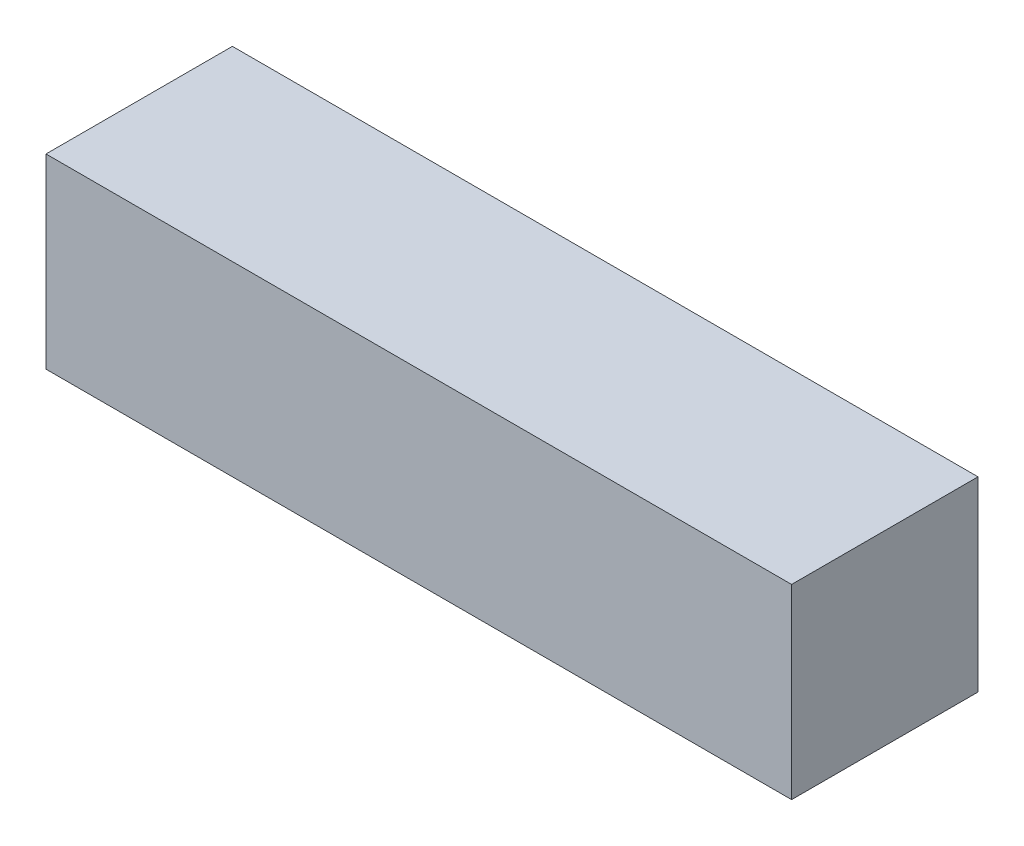
SolidWorks part; units mm, degrees
ref_plane "Front Plane" through (0, 0, 0) normal (0, 0, 1) x (1, 0, 0)
ref_plane "Top Plane" through (0, 0, 0) normal (0, 1, 0) x (1, 0, 0)
ref_plane "Right Plane" through (0, 0, 0) normal (1, 0, 0) x (0, 0, -1)
sketch "Sketch1" plane through (0, 0, 0) normal (1, 0, 0) x (0, 0, -1)
  line L1 (-4.7625, 4.7625) -> (4.7625, 4.7625)
  line L2 (-4.7625, 4.7625) -> (-4.7625, -4.7625)
  line L3 (-4.7625, -4.7625) -> (4.7625, -4.7625)
  line L4 (4.7625, 4.7625) -> (4.7625, -4.7625)
  point P4 (-4.7625, 0)
  point P5 (0, 4.7625)
  dimension "D1" = 9.525
extrude "Boss-Extrude1" add sketch "Sketch1" along normal mid plane 38.1
